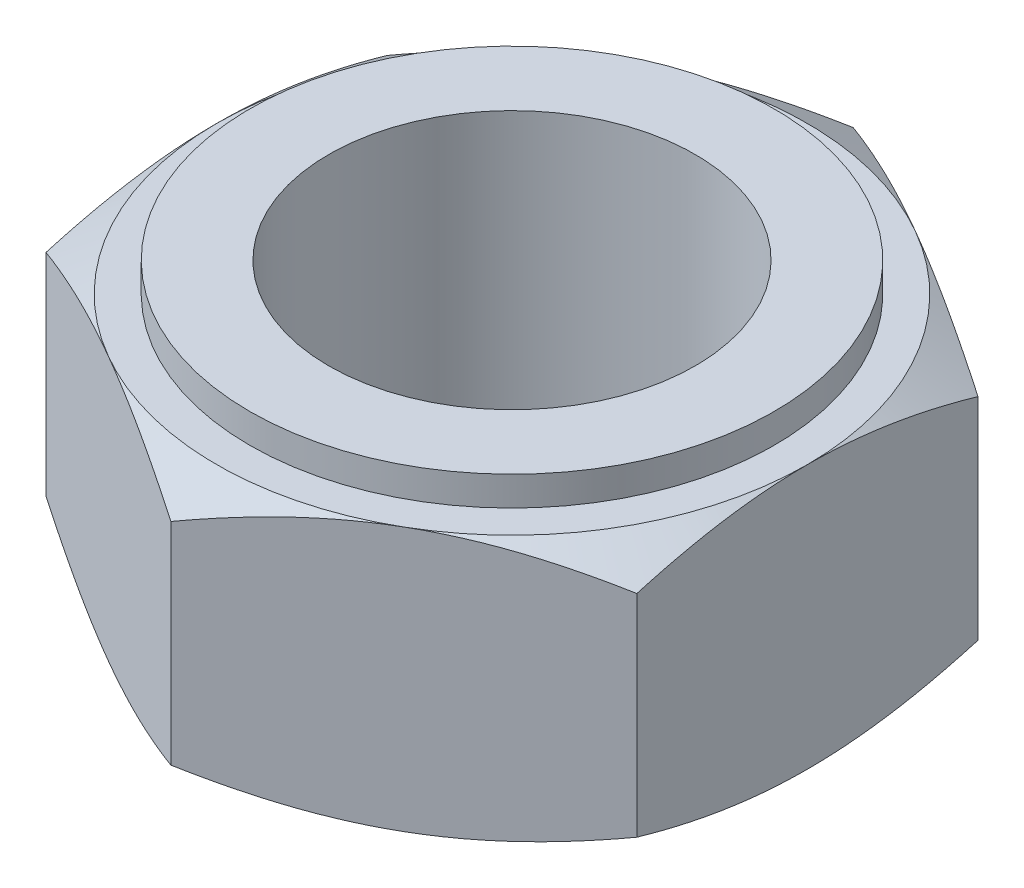
SolidWorks part; units mm, degrees
ref_plane "Front Plane" through (0, 0, 0) normal (0, 0, 1) x (1, 0, 0)
ref_plane "Top Plane" through (0, 0, 0) normal (0, 1, 0) x (1, 0, 0)
ref_plane "Right Plane" through (0, 0, 0) normal (1, 0, 0) x (0, 0, -1)
sketch "Sketch8" plane through (0, 0, 0) normal (0, 1, 0) x (1, 0, 0)
  line L0 (-6.45, 0) -> (6.45, 0) construction
  line L1 (0, 4) -> (0, -4) construction
  line L2 (0, 4) -> (-1.25, 4) construction
  line L3 (6.45, -3.2) -> (6.45, 3.2) construction
  point P4 (0, 0)
  point P8 (0, 0)
  point P11 (6.45, 0)
  dimension "Hex Size" = 12.9
  dimension "Thread Size" = 8
  dimension "Pitch" = 1.25
  dimension "Hex Height" = 6.4
sketch "Sketch1" plane through (0, 0, 0) normal (0, 1, 0) x (1, 0, 0)
  line L1 (-6.45, 3.7239) -> (-6.45, -3.7239)
  line L2 (-6.45, -3.7239) -> (0, -7.4478)
  line L3 (0, -7.4478) -> (6.45, -3.7239)
  line L4 (6.45, -3.7239) -> (6.45, 3.7239)
  line L5 (6.45, 3.7239) -> (0, 7.4478)
  line L6 (0, 7.4478) -> (-6.45, 3.7239)
  circle A0 centre (0, 0) radius 6.45 construction
  circle A1 centre (0, 0) radius 4
  dimension "Thread Size" = 8
  dimension "Hex" = 12.9
extrude "Boss-Extrude1" add sketch "Sketch1" along normal mid plane 6.4
sketch "Sketch9" plane through (0, 3.2, 0) normal (0, 1, 0) x (1, 0, 0)
  line L0 (0, -4) -> (0, -7.4478) construction
  circle A0 centre (0, 0) radius 5.7239
  circle A1 centre (0, 0) radius 4 construction
  point P8 (0, -5.7239)
extrude "Cut-Extrude3" cut sketch "Sketch9" against normal blind 0.64 flip side to cut
ref_plane "Plane1" through (0, -0.32, 0) normal (0, 1, 0) x (1, 0, 0)
sketch "Sketch5" plane through (0, 2.56, 0) normal (0, 1, 0) x (1, 0, 0)
  line L0 (-6.45, 3.7239) -> (-6.45, -3.7239) construction
  circle A1 centre (0, 0) radius 6.45
  circle A2 centre (0, 0) radius 4 construction
extrude "Cut-Extrude2" cut sketch "Sketch5" against normal through all draft 60 flip side to cut
mirror "Mirror1" about plane through (0, -0.32, 0) normal (0, 1, 0) of "Cut-Extrude2"
sketch "Sketch2" plane through (0, 3.2, 0) normal (0, 1, 0) x (1, 0, 0)
  circle A0 centre (0, 0) radius 4 construction
  circle A1 centre (0, 0) radius 4
sketch "Sketch7" plane through (0, 0, 0) normal (0, 1, 0) x (1, 0, 0)
  line L0 (0, 0) -> (2, -3.4641)
  line L1 (0, 0) -> (-4, 0) construction
  circle A0 centre (0, 0) radius 4 construction
  dimension "D1" = 120
equation "\"D3@Helix/Spiral1\"=\"Hex Height@Sketch8\"+\"Pitch@Sketch8\""
equation "\"Height@Boss-Extrude1\"=\"Hex Height@Sketch8\""
equation "\"Thread Size@Sketch1\"=\"Thread Size@Sketch8\""
equation "\"Hex@Sketch1\"=\"Hex Size@Sketch8\""
equation "\"Pitch@Helix/Spiral1\"=\"Pitch@Sketch8\""
equation "\"D1@Sketch3\"=\"Pitch@Sketch8\""
equation "\"D2@Sketch3\"=\"D1@Sketch3\"/8"
equation "\"D1@Cut-Extrude3\"=\"Hex Height@Sketch8\"*0.1"
